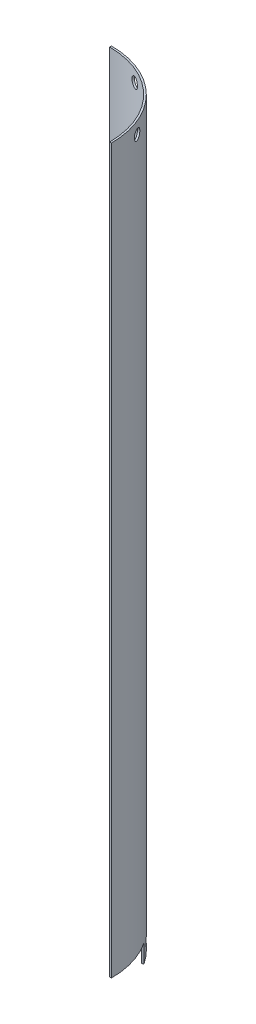
SolidWorks part; units mm, degrees
material "1060 Alloy"
ref_plane "Front Plane" through (0, 0, 0) normal (0, 0, 1) x (1, 0, 0)
ref_plane "Top Plane" through (0, 0, 0) normal (0, 1, 0) x (1, 0, 0)
ref_plane "Right Plane" through (0, 0, 0) normal (1, 0, 0) x (0, 0, -1)
sketch "Sketch1" plane through (0, 0, 0) normal (0, 1, 0) x (1, 0, 0)
  line L0 (0, 0) -> (0, 92)
  line L1 (0, 0) -> (92, 0)
  circle A0 centre (0, 0) radius 90
  circle A1 centre (0, 0) radius 92
  dimension "Internal Diameter" = 180
  dimension "External Diameter" = 184
extrude "Boss-Extrude1" add sketch "Sketch1" along normal blind 812 contours L1 A1 L0 A0
ref_plane "Plane1" through (0, 10, 0) normal (0, -1, 0) x (-1, 0, 0)
sketch "Sketch2" plane through (0, 10, 0) normal (0, -1, 0) x (-1, 0, 0)
  line L0 (0, 0) -> (-84.9969, 35.2069)
  line L1 (0, 0) -> (-65.0538, 65.0538)
  line L2 (0, 0) -> (-92, 0) construction
  line L3 (0, 0) -> (-35.2069, 84.9969)
  arc A0 (0, 92) -> (-92, 0) centre (0, 0) ccw construction
  dimension "D1" = 135
  dimension "D2" = 22.5
ref_plane "Plane2" through (84.9969, 0, -35.2069) normal (0.9239, 0, -0.3827) x (-0.3827, 0, -0.9239)
ref_plane "Plane3" through (35.2069, 0, -84.9969) normal (0.3827, 0, -0.9239) x (-0.9239, 0, -0.3827)
sketch "Sketch3" plane through (84.9969, 0, -35.2069) normal (0.9239, 0, -0.3827) x (-0.3827, 0, -0.9239)
  circle A0 centre (0, 10) radius 5.565
  point P0 (0, 10)
  dimension "Left Hole Diameter" = 11.13
sketch "Sketch5" plane through (35.2069, 0, -84.9969) normal (0.3827, 0, -0.9239) x (-0.9239, 0, -0.3827)
  line L0 (0, 10) -> (-84.9969, 10) construction
  circle A0 centre (0, 10) radius 5.565
  dimension "Right Hole Diameter" = 11.13
ref_plane "Plane4" through (65.0538, 0, -65.0538) normal (0.7071, 0, -0.7071) x (-0.7071, 0, -0.7071)
sketch "Sketch6" plane through (65.0538, 0, -65.0538) normal (0.7071, 0, -0.7071) x (-0.7071, 0, -0.7071)
  line L0 (0, 10) -> (-65.0538, 10) construction
  line L1 (0, 10) -> (35.2069, 10) construction
  circle A0 centre (0, 10) radius 5.565
  dimension "Middle Hole Diameter" = 11.13
extrude "Cut-Extrude4" cut sketch "Sketch6" against normal up to surface (2.1722 mm away)
extrude "Cut-Extrude2" cut sketch "Sketch3" against normal up to surface (2.1722 mm away) contours A0
extrude "Cut-Extrude3" cut sketch "Sketch5" against normal up to surface (2.1722 mm away) contours A0
pattern_linear "LPattern2" count 2 spacing 789 along (0, 1, 0) of "Cut-Extrude2", "Cut-Extrude3"
sketch "Sketch7" plane through (0, 0, 0) normal (0, -1, 0) x (1, 0, 0)
  line L0 (0, 0) -> (65.0538, -65.0538) construction
  line L1 (0.3118, -0.3118) -> (57.9282, -0.3118) construction
  line L2 (0.3118, -0.3118) -> (76.4474, -51.184)
  line L3 (0.3118, -0.3118) -> (51.184, -76.4474)
  line L6 (92, 0) -> (90, 0)
  line L7 (0, -90) -> (0, -92)
  line L8 (92, 0) -> (90, 0)
  line L9 (0, -90) -> (0, -92)
  arc A0 (0, -92) -> (92, 0) centre (0, 0) ccw construction
  arc A2 (0, -90) -> (90, 0) centre (0, 0) ccw
  arc A3 (0, -92) -> (92, 0) centre (0, 0) ccw
  arc A4 (0, -90) -> (90, 0) centre (0, 0) ccw
  arc A5 (0, -92) -> (92, 0) centre (0, 0) ccw
  line M4 (92, 0) -> (90, 0)
  arc M5 (90, 0) -> (0, -90) centre (0, 0) cw
  line M6 (0, -90) -> (0, -92)
  arc M7 (0, -92) -> (92, 0) centre (0, 0) ccw
  dimension "D1" = 45
  dimension "D2" = 11.25
  dimension "D3" = 0
extrude "Cut-Extrude5" cut sketch "Sketch7" against normal blind 20 contours L2 M5 M7 M4 | L3 M5 M6 M7 | A4 L8 A5 L9
equation "\"Total Panel Length\"= 812"
equation "\"Internal Panel Diameter\"= 180"
equation "\"External Panel Diameter\"= 184"
equation "\"L & R Mounting Hole Diameter\"= 11.13"
equation "\"M Mounting Hole DIameter\"= 11.13"
equation "\"Mounting Hole Dist. from Top\"= 13"
equation "\"Mounting Hole Dist. from Base\"= 10"
equation "\"External Diameter@Sketch1\"= \"External Panel Diameter\""
equation "\"Internal Diameter@Sketch1\"= \"Internal Panel Diameter\""
equation "\"Panel Length@Boss-Extrude1\"= \"Total Panel Length\""
equation "\"Left Hole Diameter@Sketch3\" = \"L & R Mounting Hole Diameter\""
equation "\"Right Hole Diameter@Sketch5\" = \"L & R Mounting Hole Diameter\""
equation "\"Middle Hole Diameter@Sketch6\" = \"M Mounting Hole DIameter\""
equation "\"Mounting from Base@Plane1\" = \"Mounting Hole Dist. from Base\""
equation "\"Mounting from Top@LPattern2\"= \"Total Panel Length\" - \"Mounting Hole Dist. from Base\" - \"Mounting Hole Dist. from Top\""
equation "\"Base Tab Length@Cut-Extrude5\" = \"Base Tab Length\""
equation "\"Base Tab Length\"= 20"
